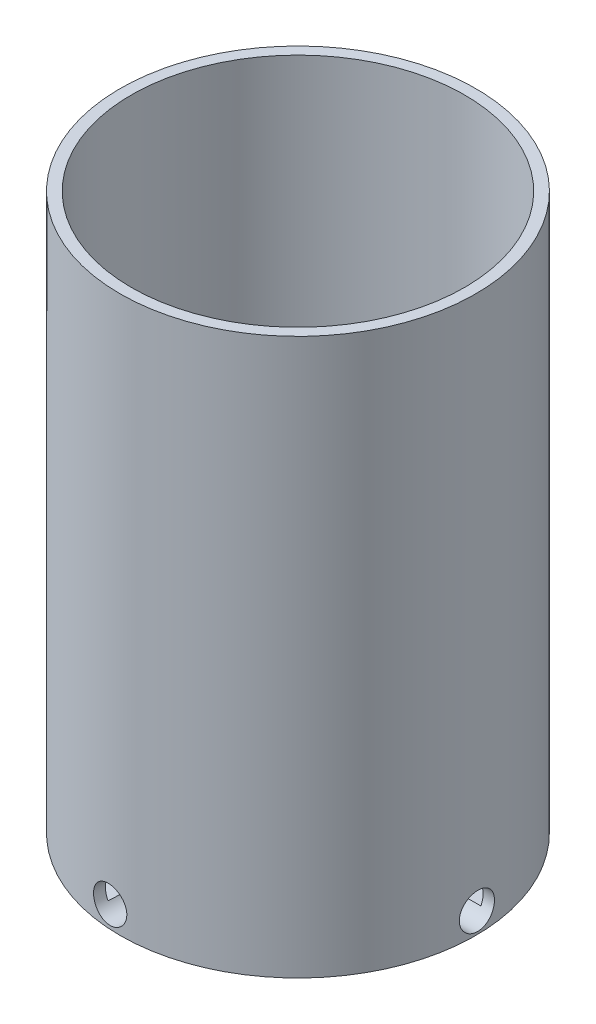
SolidWorks part; units mm, degrees
ref_plane "Front Plane" through (0, 0, 0) normal (0, 0, 1) x (1, 0, 0)
ref_plane "Top Plane" through (0, 0, 0) normal (0, 1, 0) x (1, 0, 0)
ref_plane "Right Plane" through (0, 0, 0) normal (1, 0, 0) x (0, 0, -1)
sketch "Sketch1" plane through (0, 0, 0) normal (0, 1, 0) x (1, 0, 0)
  circle A0 centre (0, 0) radius 80
extrude "Boss-Extrude1" add sketch "Sketch1" along normal blind 250
shell "Shell3" thickness 5
hole_wizard "Ø16.0mm Dowel Hole1" positions "3DSketch3" profile "Sketch4" hole size "Ø16.0" standard "ANSI Metric"
sketch3d "3DSketch3"
  point P0 (79.9948, 9.1364, -0.9108)
  point P2 (0, 0, 0)
  point P5 (-5.0517, 9.5264, 79.8403)
sketch "Sketch4" plane through (79.9948, 9.1364, -0.9108) normal (0, 1, 0) x (-0.0114, 0, -0.9999)
  line L0 (0, 0) -> (0, 160.9057)
  line L1 (0, 160.9057) -> (8, 160.9057)
  line L2 (8, 160.9057) -> (8, 0)
  line L5 (8, 0) -> (0, 0)
  line L11 (0, -6.35) -> (0, 107.95) construction
  dimension "Thru Hole Dia." = 16
  dimension "Thru Hole Depth" = 160.9057
